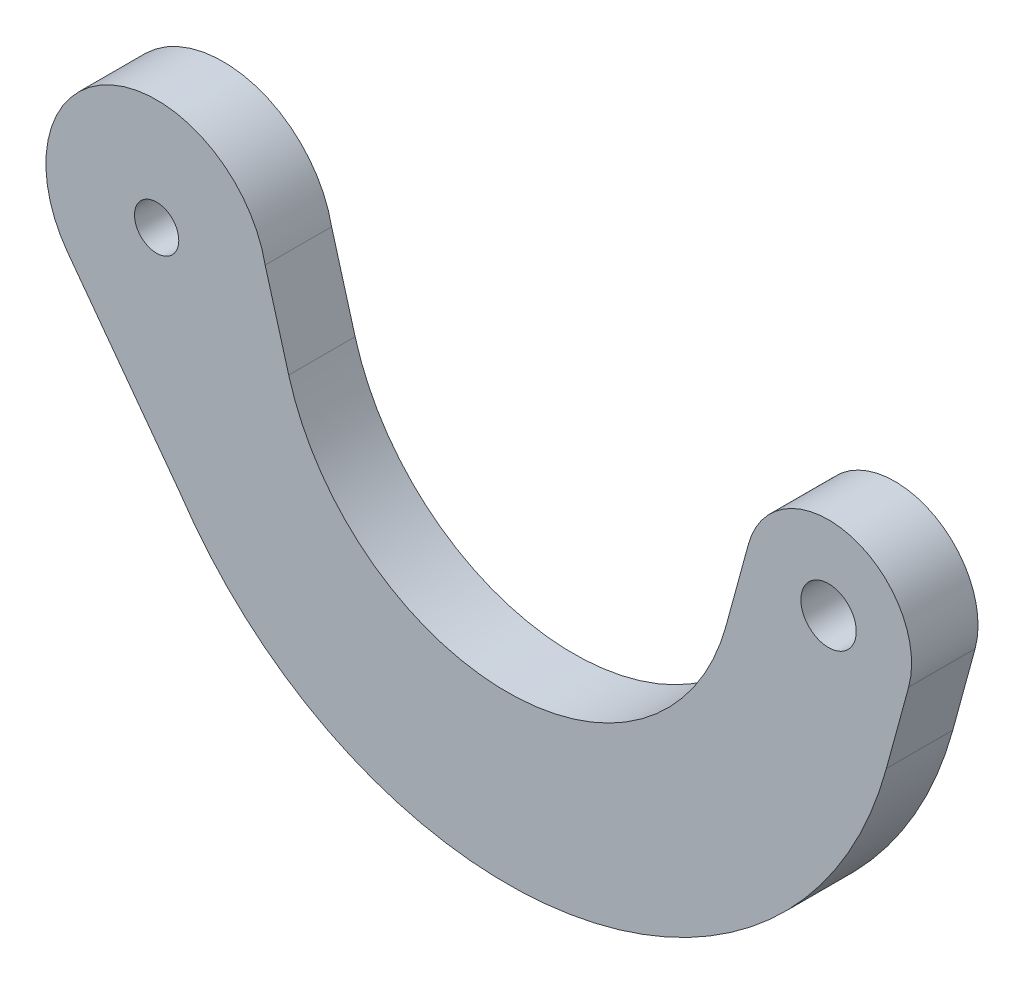
SolidWorks part; units mm, degrees
ref_plane "Front Plane" through (0, 0, 0) normal (0, 0, 1) x (1, 0, 0)
ref_plane "Top Plane" through (0, 0, 0) normal (0, 1, 0) x (1, 0, 0)
ref_plane "Right Plane" through (0, 0, 0) normal (1, 0, 0) x (0, 0, -1)
sketch "Sketch1" plane through (0, 0, 0) normal (0, 0, 1) x (1, 0, 0)
  line L0 (0, 0) -> (15.6824, -28.2918) construction
  line L1 (0, 0) -> (60.683, 0) construction
  line L2 (53.4477, 1.9749) -> (51.4352, -5.398)
  line L3 (67.9183, -1.9749) -> (65.9059, -9.3478)
  line L4 (9.8031, 1.9749) -> (11.9277, -5.562)
  line L5 (-8.0411, -5.9448) -> (2.1108, -19.6766)
  arc A0 (9.8031, 1.9749) -> (-8.0411, -5.9448) centre (0, 0) ccw
  arc A1 (67.9183, -1.9749) -> (53.4477, 1.9749) centre (60.683, 0) ccw
  arc A2 (11.9277, -5.562) -> (51.4352, -5.398) centre (31.6587, 0) ccw
  arc A3 (2.1108, -19.6766) -> (65.9059, -9.3478) centre (31.6587, 0) ccw
  circle A4 centre (0, 0) radius 2
  circle A5 centre (60.683, 0) radius 2.5
  dimension "D1" = 20
  dimension "D2" = 15
  dimension "D5" = 71
  dimension "D6" = 41
  dimension "D7" = 4
  dimension "D8" = 5
  dimension "D3" = 60.683
  dimension "D4" = 61
extrude "Boss-Extrude1" add sketch "Sketch1" along normal blind 6
